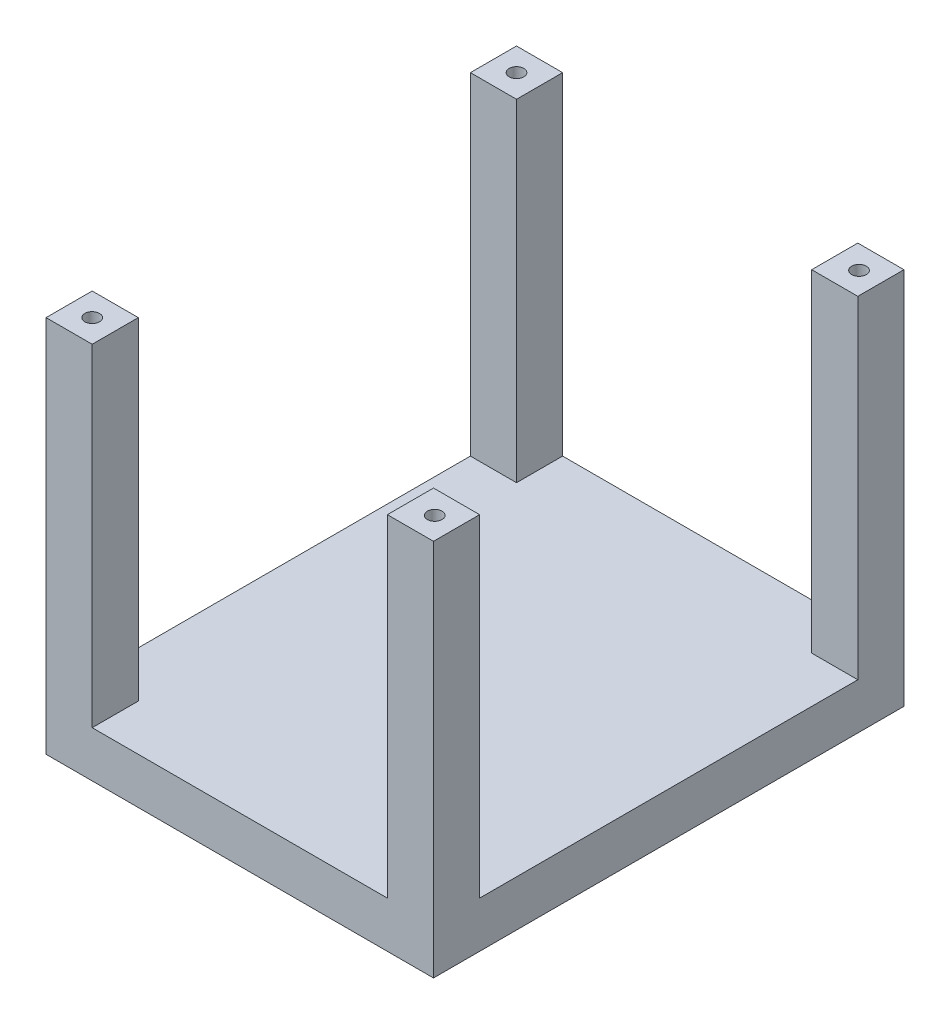
SolidWorks part; units mm, degrees
ref_plane "Alzado" through (0, 0, 0) normal (0, 0, 1) x (1, 0, 0)
ref_plane "Planta" through (0, 0, 0) normal (0, 1, 0) x (1, 0, 0)
ref_plane "Vista lateral" through (0, 0, 0) normal (1, 0, 0) x (0, 0, -1)
sketch "Croquis1" plane through (0, 0, 0) normal (0, 1, 0) x (1, 0, 0)
  line L1 (-21.0659, 11.644) -> (-16.0659, 11.644)
  line L2 (-21.0659, 11.644) -> (-21.0659, 6.644)
  line L3 (-21.0659, 6.644) -> (-16.0659, 6.644)
  line L4 (-16.0659, 11.644) -> (-16.0659, 6.644)
  line L5 (15.9341, 11.644) -> (20.9341, 11.644)
  line L6 (15.9341, 11.644) -> (15.9341, 6.644)
  line L7 (15.9341, 6.644) -> (20.9341, 6.644)
  line L8 (20.9341, 11.644) -> (20.9341, 6.644)
  line L9 (-21.0659, -34.356) -> (-16.0659, -34.356)
  line L10 (-21.0659, -34.356) -> (-21.0659, -39.356)
  line L11 (-21.0659, -39.356) -> (-16.0659, -39.356)
  line L12 (-16.0659, -34.356) -> (-16.0659, -39.356)
  line L13 (15.9341, -34.356) -> (20.9341, -34.356)
  line L14 (15.9341, -34.356) -> (15.9341, -39.356)
  line L15 (15.9341, -39.356) -> (20.9341, -39.356)
  line L16 (20.9341, -34.356) -> (20.9341, -39.356)
  point P16 (-16.0659, 9.144)
  point P17 (-21.0659, 9.144)
  dimension "D1" = 5
  dimension "D2" = 5
  dimension "D3" = 5
  dimension "D4" = 5
  dimension "D5" = 0
  dimension "D6" = 32
  dimension "D7" = 5
  dimension "D8" = 5
  dimension "D9" = 0
  dimension "D10" = 41
  dimension "D11" = 5
  dimension "D12" = 5
  dimension "D13" = 0
  dimension "D14" = 41
extrude "Saliente-Extruir1" add sketch "Croquis1" along normal blind 41
sketch "Croquis2" plane through (0, 0, 0) normal (0, 1, 0) x (1, 0, 0)
  line L1 (-21.0659, 11.644) -> (20.9341, 11.644)
  line L2 (-21.0659, 11.644) -> (-21.0659, -39.356)
  line L3 (-21.0659, -39.356) -> (20.9341, -39.356)
  line L4 (20.9341, 11.644) -> (20.9341, -39.356)
  dimension "D1" = 42
  dimension "D2" = 51
extrude "Saliente-Extruir2" add sketch "Croquis2" along normal blind 5
sketch "Croquis3" plane through (0, 41, 0) normal (0, 1, 0) x (1, 0, 0)
  line L0 (-16.0659, 6.644) -> (-16.0659, 11.644) construction
  line L1 (-16.0659, 11.644) -> (-21.0659, 11.644) construction
  line L4 (-16.0659, -34.356) -> (-16.0659, -39.356) construction
  line L5 (-21.0659, -39.356) -> (-16.0659, -39.356) construction
  circle A0 centre (-18.5659, 9.144) radius 0.7937
  circle A1 centre (-18.5659, -36.856) radius 0.7937
  point P10 (0, 0)
  dimension "D1" = 1.5875
  dimension "D4" = 1.5875
  dimension "D2" = 2.5
  dimension "D3" = 2.5
  dimension "D5" = 2.5
  dimension "D6" = 2.5
extrude "Cortar-Extruir1" cut sketch "Croquis3" against normal blind 41
mirror "Simetría1" about plane through (0, 0, 0) normal (1, 0, 0) of "Cortar-Extruir1"
